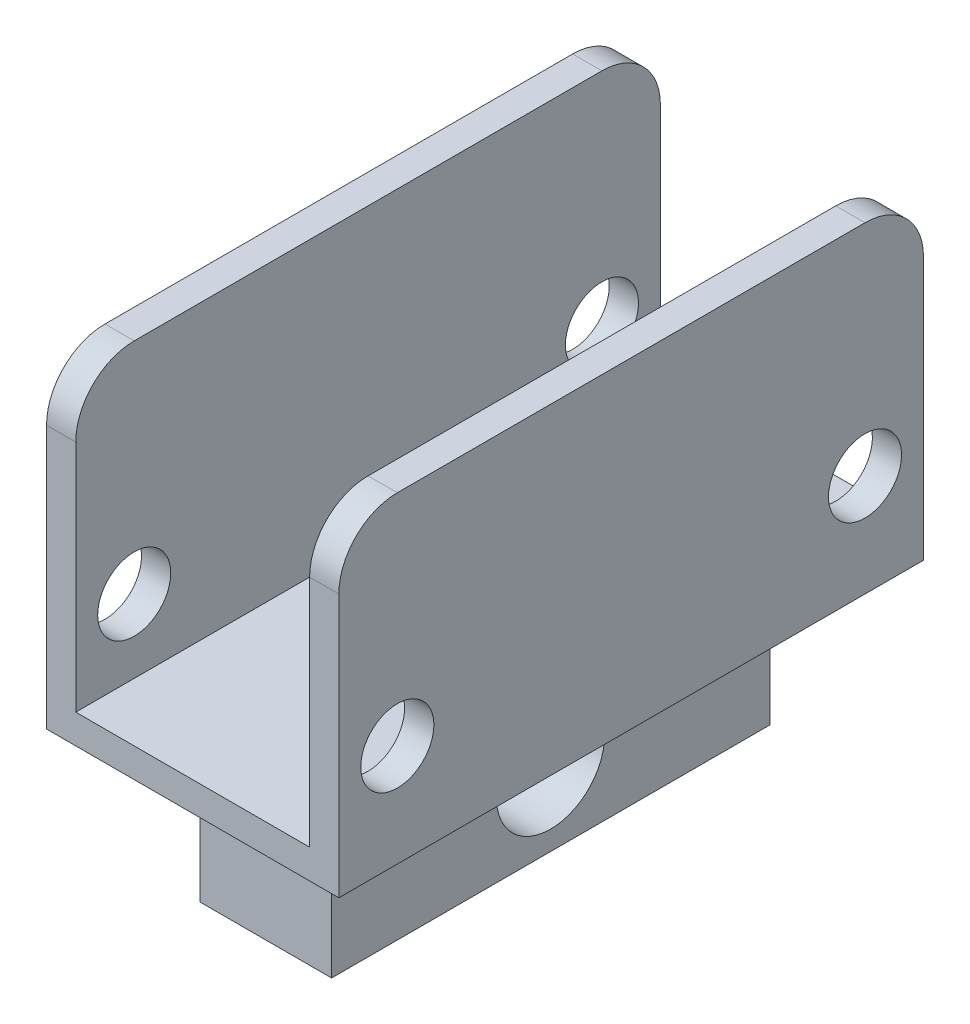
SolidWorks part; units mm, degrees
ref_plane "Front Plane" through (0, 0, 0) normal (0, 0, 1) x (1, 0, 0)
ref_plane "Top Plane" through (0, 0, 0) normal (0, 1, 0) x (1, 0, 0)
ref_plane "Right Plane" through (0, 0, 0) normal (1, 0, 0) x (0, 0, -1)
sketch "Sketch1" plane through (0, 0, 0) normal (0, 0, 1) x (1, 0, 0)
  line L0 (10.16, 0) -> (-10.16, 0)
  line L1 (-10.16, 0) -> (-10.16, 25.4)
  line L2 (0, 0) -> (0, 18.0821) construction
  line L3 (10.16, 0) -> (10.16, 25.4)
  dimension "D1" = 10.16
  dimension "D2" = 25.4
extrude "Extrude-Thin1" add sketch "Sketch1" along normal blind 50.8 thin thin type one direction wall 2.54
sketch "Sketch2" plane through (-12.7, 0, 0) normal (-1, 0, 0) x (0, 0, 1)
  line L0 (0, 0) -> (52.4542, 0) construction
  line L2 (0, 0) -> (0, 25.4) construction
  line L4 (50.8, 25.4) -> (0, 25.4) construction
  circle A0 centre (45.72, 6.35) radius 3.175
  circle A1 centre (5.08, 6.35) radius 3.175
  point P13 (25.4, 25.4)
  point P17 (0, 12.7)
  dimension "D4" = 6.35
  dimension "D1" = 5.08
  dimension "D2" = 40.64
  dimension "D3" = 6.35
fillet "Fillet1" radius 5.08 4 edges at (11.43, 25.4, 50.8) (-11.43, 25.4, 50.8) (-11.43, 25.4, 0) (11.43, 25.4, 0)
extrude "Cut-Extrude1" cut sketch "Sketch2" against normal through all
sketch "Sketch3" plane through (0, -2.54, 0) normal (0, -1, 0) x (1, 0, 0)
  line L0 (0, 52.6767) -> (0, -4.5846) construction
  line L1 (5.72, 6.35) -> (-5.72, 6.35)
  line L2 (-5.72, 6.35) -> (-5.72, 44.45)
  line L3 (-5.72, 44.45) -> (5.72, 44.45)
  line L4 (-12.7, 25.4) -> (12.7, 25.4) construction
  line L5 (-12.7, 50.8) -> (-12.7, 0) construction
  line L6 (12.7, 50.8) -> (12.7, 0) construction
  line L7 (-12.7, 50.8) -> (12.7, 50.8) construction
  line L8 (5.72, 6.35) -> (5.72, 44.45)
  point P13 (-5.72, 25.4)
  point P17 (0, 6.35)
  point P18 (0, 44.45)
  dimension "D1" = 5.72
  dimension "D2" = 38.1
  dimension "D3" = 6.35
extrude "Boss-Extrude1" add sketch "Sketch3" along normal blind 12.7
sketch "Sketch4" plane through (5.72, 0, 0) normal (1, 0, 0) x (0, 0, -1)
  line L0 (-25.4261, -8.8526) -> (-54.8961, -29.4878) construction
  line L1 (-44.45, -15.24) -> (-6.35, -15.24) construction
  circle A0 centre (-25.4261, -8.8526) radius 4.699
  dimension "D1" = 9.398
  dimension "D2" = 35
extrude "Cut-Extrude2" cut sketch "Sketch4" against normal through all
